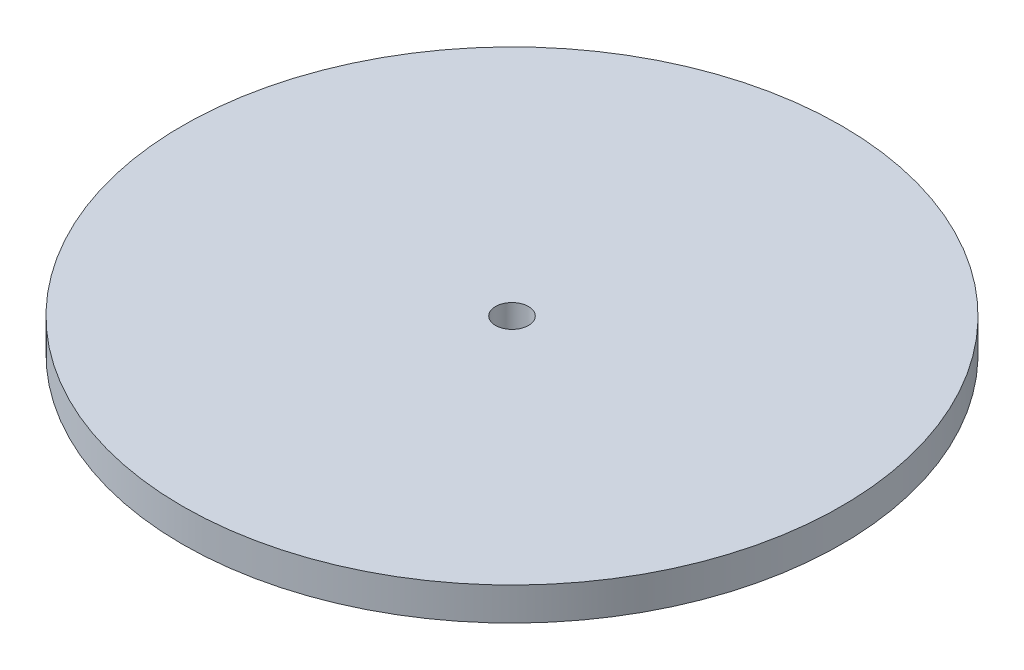
SolidWorks part; units mm, degrees
ref_plane "Front Plane" through (0, 0, 0) normal (0, 0, 1) x (1, 0, 0)
ref_plane "Top Plane" through (0, 0, 0) normal (0, 1, 0) x (1, 0, 0)
ref_plane "Right Plane" through (0, 0, 0) normal (1, 0, 0) x (0, 0, -1)
sketch "Sketch1" plane through (0, 0, 0) normal (0, 1, 0) x (1, 0, 0)
  circle A0 centre (0, 0) radius 101.6
extrude "Boss-Extrude1" add sketch "Sketch1" along normal blind 10.16
sketch "Sketch2" plane through (0, 10.16, 0) normal (0, 1, 0) x (1, 0, 0)
  circle A0 centre (0, 0) radius 5.08
extrude "Cut-Extrude1" cut sketch "Sketch2" against normal blind 10.16
